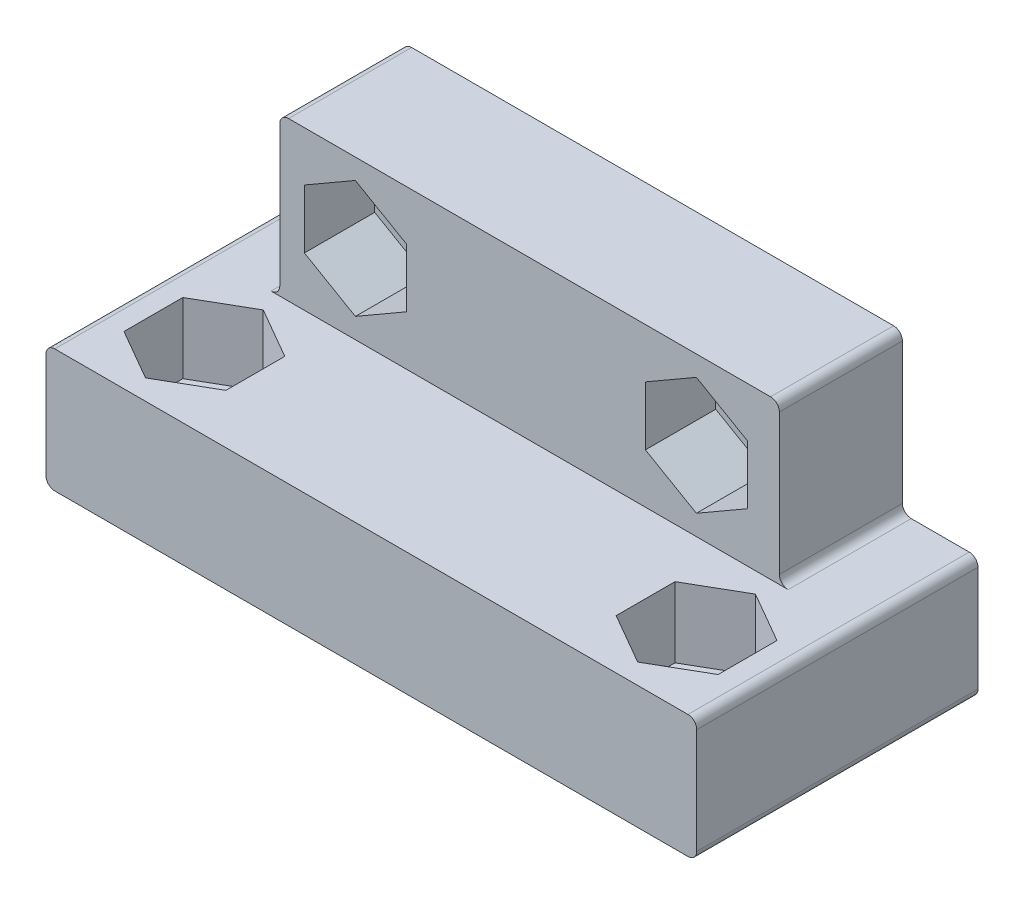
SolidWorks part; units mm, degrees
ref_plane "Front Plane" through (0, 0, 0) normal (0, 0, 1) x (1, 0, 0)
ref_plane "Top Plane" through (0, 0, 0) normal (0, 1, 0) x (1, 0, 0)
ref_plane "Right Plane" through (0, 0, 0) normal (1, 0, 0) x (0, 0, -1)
sketch "Sketch1" plane through (0, 0, 0) normal (0, 0, 1) x (1, 0, 0)
  line L30 (36.52, 7) -> (33.22, 7)
  line L31 (32.72, 7.5) -> (32.72, 15.5)
  line L32 (36.52, 0) -> (0.5, 0)
  line L33 (4.3, 7.5) -> (4.3, 15.5)
  line L34 (3.8, 7) -> (0.5, 7)
  line L35 (4.8, 16) -> (32.22, 16)
  line L36 (0, 6.5) -> (0, 0.5)
  line L37 (37.02, 0.5) -> (37.02, 6.5)
  arc A4 (0.5, 0) -> (0, 0.5) centre (0.5, 0.5) cw
  circle A12 centre (8.81, 11.5) radius 1.65
  circle A13 centre (28.21, 11.5) radius 1.65
  arc A14 (37.02, 6.5) -> (36.52, 7) centre (36.52, 6.5) ccw
  arc A15 (36.52, 0) -> (37.02, 0.5) centre (36.52, 0.5) ccw
  arc A16 (0.5, 7) -> (0, 6.5) centre (0.5, 6.5) ccw
  arc A17 (4.3, 7.5) -> (3.8, 7) centre (3.8, 7.5) cw
  arc A18 (4.3, 15.5) -> (4.8, 16) centre (4.8, 15.5) cw
  arc A19 (32.72, 15.5) -> (32.22, 16) centre (32.22, 15.5) ccw
  arc A20 (32.72, 7.5) -> (33.22, 7) centre (33.22, 7.5) ccw
extrude "Boss-Extrude1" add sketch "Sketch1" along normal blind 16
sketch "Sketch2" plane through (0, 0, 16) normal (0, 0, 1) x (1, 0, 0)
  line L0 (33.22, 7) -> (3.8, 7)
  line L5 (4.3, 16) -> (32.72, 16)
  line L6 (4.3, 16) -> (4.3, 7.5)
  line L8 (32.72, 16) -> (32.72, 7.5)
  arc A0 (3.8, 7) -> (4.3, 7.5) centre (3.8, 7.5) ccw
  arc A1 (32.72, 7.5) -> (33.22, 7) centre (33.22, 7.5) ccw
extrude "Cut-Extrude1" cut sketch "Sketch2" against normal offset from surface (9 mm away) 7 up to face at (10.46, 11.5, 0)
sketch "Sketch3" plane through (0, 0, 7) normal (0, 0, 1) x (1, 0, 0)
  line L0 (8.6, 8.1514) -> (11.5, 9.8257)
  line L1 (11.5, 9.8257) -> (11.5, 13.1743)
  line L2 (11.5, 13.1743) -> (8.6, 14.8486)
  line L3 (8.6, 14.8486) -> (5.7, 13.1743)
  line L4 (5.7, 13.1743) -> (5.7, 9.8257)
  line L5 (5.7, 9.8257) -> (8.6, 8.1514)
  line L6 (28, 8.1514) -> (30.9, 9.8257)
  line L7 (30.9, 9.8257) -> (30.9, 13.1743)
  line L8 (30.9, 13.1743) -> (28, 14.8486)
  line L9 (28, 14.8486) -> (25.1, 13.1743)
  line L10 (25.1, 13.1743) -> (25.1, 9.8257)
  line L11 (25.1, 9.8257) -> (28, 8.1514)
  circle A0 centre (8.6, 11.5) radius 2.9 construction
  circle A1 centre (28, 11.5) radius 2.9 construction
extrude "Cut-Extrude2" cut sketch "Sketch3" against normal offset from surface (4 mm away) 3 up to face at (10.46, 11.5, 0)
sketch "Sketch4" plane through (0, 7, 0) normal (0, 1, 0) x (1, 0, 0)
  circle A6 centre (32.51, -11.5) radius 1.65
  circle A7 centre (4.51, -11.5) radius 1.65
extrude "Cut-Extrude3" cut sketch "Sketch4" against normal up to surface (7 mm away) up to face at (18.51, 0, 8)
sketch "Sketch5" plane through (0, 7, 0) normal (0, 1, 0) x (1, 0, 0)
  line L0 (32.51, -14.8486) -> (35.41, -13.1743)
  line L1 (35.41, -13.1743) -> (35.41, -9.8257)
  line L2 (35.41, -9.8257) -> (32.51, -8.1514)
  line L3 (32.51, -8.1514) -> (29.61, -9.8257)
  line L4 (29.61, -9.8257) -> (29.61, -13.1743)
  line L5 (29.61, -13.1743) -> (32.51, -14.8486)
  line L6 (4.51, -14.8486) -> (7.41, -13.1743)
  line L7 (7.41, -13.1743) -> (7.41, -9.8257)
  line L8 (7.41, -9.8257) -> (4.51, -8.1514)
  line L9 (4.51, -8.1514) -> (1.61, -9.8257)
  line L10 (1.61, -9.8257) -> (1.61, -13.1743)
  line L11 (1.61, -13.1743) -> (4.51, -14.8486)
  circle A0 centre (32.51, -11.5) radius 2.9 construction
  circle A1 centre (4.51, -11.5) radius 2.9 construction
extrude "Cut-Extrude4" cut sketch "Sketch5" against normal offset from surface (4 mm away) 3 up to face at (30.86, 0, 11.5)
